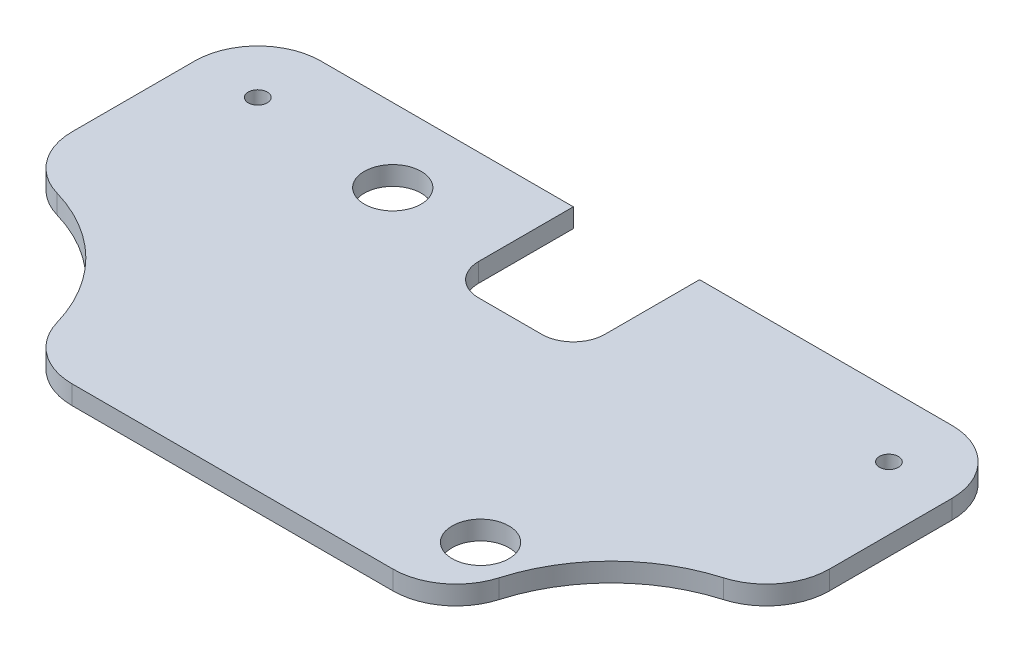
SolidWorks part; units mm, degrees
ref_plane "前视基准面" through (0, 0, 0) normal (0, 0, 1) x (1, 0, 0)
ref_plane "上视基准面" through (0, 0, 0) normal (0, 1, 0) x (1, 0, 0)
ref_plane "右视基准面" through (0, 0, 0) normal (1, 0, 0) x (0, 0, -1)
sketch "草图1" plane through (0, 0, 0) normal (0, 1, 0) x (1, 0, 0)
  line L1 (-60, -32) -> (60, -32)
  line L2 (-60, -32) -> (-60, 32)
  line L3 (-60, 32) -> (60, 32)
  line L4 (60, -32) -> (60, 32)
  line L5 (-60, -32) -> (60, 32) construction
  line L6 (-60, 32) -> (60, -32) construction
  point P0 (0, 0)
  dimension "D1" = 120
  dimension "D2" = 64
extrude "凸台-拉伸1" add sketch "草图1" along normal blind 3
sketch "草图2" plane through (0, 3, 0) normal (0, 1, 0) x (1, 0, 0)
  line L0 (-60, 22) -> (60, 22) construction
  line L1 (-60, 32) -> (-60, -32) construction
  line L2 (60, -32) -> (60, 32) construction
  line L3 (60, 32) -> (-60, 32) construction
  line L4 (0, 32) -> (0, -32) construction
  line L5 (-60, -32) -> (60, -32) construction
  circle A1 centre (-50, 22) radius 1.5
  circle A2 centre (50, 22) radius 1.5
  dimension "D4" = 3
  dimension "D1" = 10
  dimension "D3" = 50
extrude "切除-拉伸1" cut sketch "草图2" against normal blind 3
fillet "圆角1" radius 10 2 edges at (60, 1.5, -32) (-60, 1.5, -32)
sketch "草图3" plane through (0, 0, 0) normal (0, -1, 0) x (1, 0, 0)
  line L0 (50, -32) -> (-50, -32) construction
  line L1 (-10, -32) -> (10, -32)
  line L2 (-10, -32) -> (-10, -12)
  line L3 (-10, -12) -> (10, -12)
  line L4 (10, -32) -> (10, -12)
  line L5 (0, 32) -> (0, -32) construction
  line L6 (-60, 32) -> (60, 32) construction
  dimension "D1" = 20
  dimension "D2" = 20
extrude "切除-拉伸2" cut sketch "草图3" against normal blind 3
sketch "草图4" plane through (0, 0, 0) normal (0, -1, 0) x (1, 0, 0)
  line L0 (0, -12) -> (0, 32) construction
  line L1 (10, -12) -> (-10, -12) construction
  line L2 (-60, 32) -> (60, 32) construction
  circle A0 centre (-60, 32) radius 26
  circle A1 centre (60, 32) radius 26
  dimension "D1" = 52
extrude "切除-拉伸3" cut sketch "草图4" against normal blind 3
fillet "圆角2" radius 5 2 edges at (10, 1.5, -12) (-10, 1.5, -12)
fillet "圆角3" radius 10 2 edges at (60, 1.5, 6) (-60, 1.5, 6)
fillet "圆角4" radius 10 2 edges at (34, 1.5, 32) (-34, 1.5, 32)
extrude "切除-拉伸4" cut sketch "草图5" against normal blind 3
sketch "草图5" [suppressed] plane through (-51.1463, 3, 257.5) normal (0, 1, 0) x (-1, 0, 0)
  circle A0 centre (-16.7472, -272.4841) radius 2.1
  circle A1 centre (-67.4628, -249.3327) radius 2.1
  circle A2 centre (-65.252, -245.0006) radius 2.1
extrude "切除-拉伸5" cut sketch "草图6" against normal blind 6
sketch "草图6" plane through (0, 6, 189.1463) normal (0, 1, 0) x (0, 0, 1)
  circle A0 centre (-209.4559, -26.9214) radius 2.1
  circle A1 centre (-167.7622, 28.6833) radius 2.1
sketch "草图7" plane through (0, 0, 0) normal (0, -1, 0) x (1, 0, 0)
  circle A0 centre (-26.9214, -20.3096) radius 4.5
  circle A1 centre (28.6833, 21.3841) radius 4.5
  dimension "D1" = 9
  dimension "D2" = 9
extrude "切除-拉伸6" cut sketch "草图7" against normal blind 3
